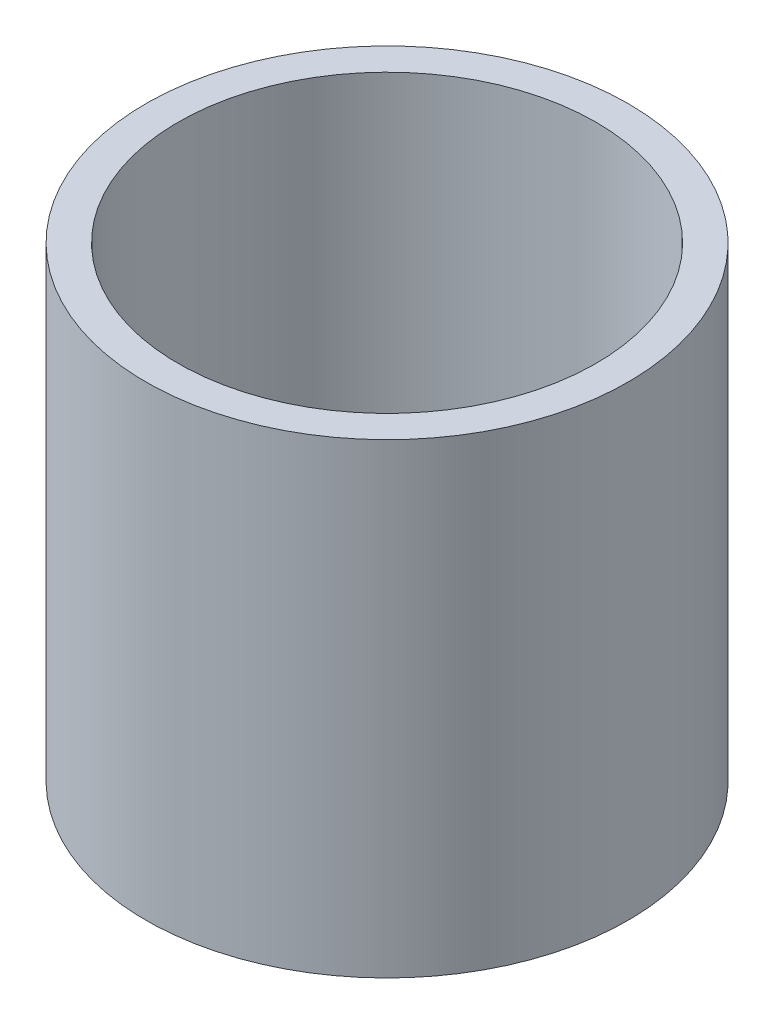
SolidWorks part; units mm, degrees
ref_plane "Front Plane" through (0, 0, 0) normal (0, 0, 1) x (1, 0, 0)
ref_plane "Top Plane" through (0, 0, 0) normal (0, 1, 0) x (1, 0, 0)
ref_plane "Right Plane" through (0, 0, 0) normal (1, 0, 0) x (0, 0, -1)
sketch "Sketch1" plane through (0, 0, 0) normal (0, 0, 1) x (1, 0, 0)
  line L0 (0, 0) -> (0, 0.8)
  line L1 (0, 0.8) -> (1.8, 0.8)
  line L2 (2.6, 1.6) -> (2.6, 5.8)
  line L3 (2.6, 5.8) -> (3, 5.8)
  line L4 (3, 5.8) -> (3, 0)
  line L5 (3, 0) -> (0, 0)
  arc A0 (1.8, 0.8) -> (2.6, 1.6) centre (1.8, 1.6) ccw
  point P9 (2.6, 0.8)
  dimension "D5" = 0.8
  dimension "D1" = 0.8
  dimension "D2" = 0.4
  dimension "D3" = 5
  dimension "D4" = 3
revolve "Revolve1" add sketch "Sketch1" angle 360 about L0
